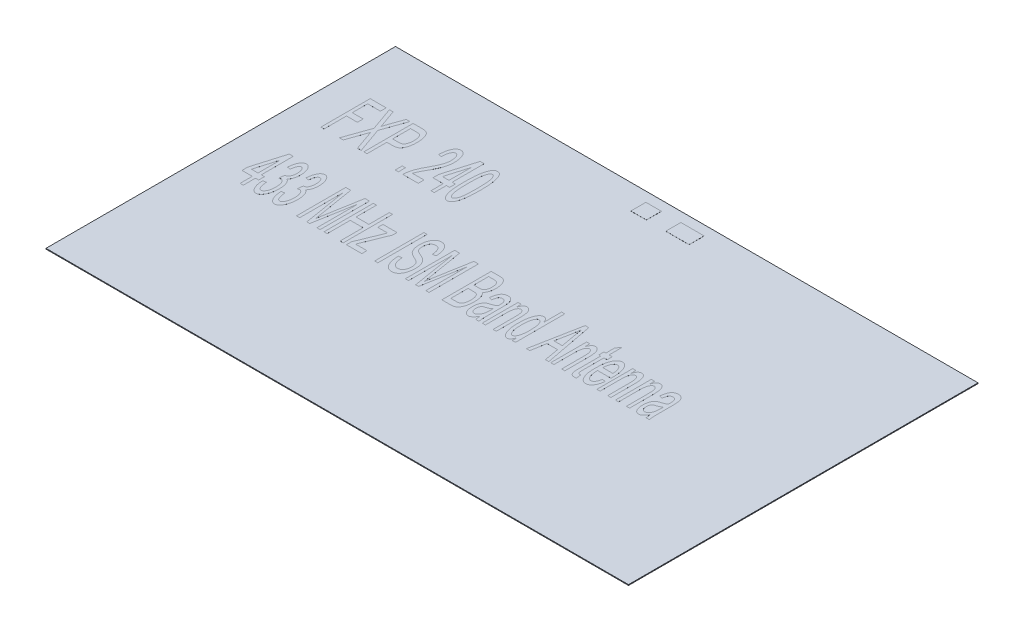
SolidWorks part; units mm, degrees
ref_plane "Front" through (0, 0, 0) normal (0, 0, 1) x (1, 0, 0)
ref_plane "Top" through (0, 0, 0) normal (0, 1, 0) x (1, 0, 0)
ref_plane "Right" through (0, 0, 0) normal (1, 0, 0) x (0, 0, -1)
sketch "Sketch1" plane through (0, 0, 0) normal (0, 1, 0) x (1, 0, 0)
  line L1 (-37.5, -22.5) -> (37.5, -22.5)
  line L2 (-37.5, -22.5) -> (-37.5, 22.5)
  line L3 (-37.5, 22.5) -> (37.5, 22.5)
  line L4 (37.5, -22.5) -> (37.5, 22.5)
  line L5 (-37.5, -22.5) -> (37.5, 22.5) construction
  line L6 (-37.5, 22.5) -> (37.5, -22.5) construction
  point P0 (0, 0)
  dimension "D1" = 75
  dimension "D2" = 45
extrude "Boss-Extrude1" add sketch "Sketch1" along normal blind 0.1
sketch "Sketch2" plane through (0, 0.1, 0) normal (0, 1, 0) x (1, 0, 0)
  line L1 (-4, 21.2387) -> (-2, 21.2387)
  line L2 (-4, 21.2387) -> (-4, 19.3008)
  line L3 (-4, 19.3008) -> (-2, 19.3008)
  line L4 (-2, 21.2387) -> (-2, 19.3008)
  line L5 (-4, 21.2387) -> (-2, 19.3008) construction
  line L6 (-4, 19.3008) -> (-2, 21.2387) construction
  line L7 (0.5, 21.2387) -> (3.5, 21.2387)
  line L8 (0.5, 21.2387) -> (0.5, 19.3008)
  line L9 (0.5, 19.3008) -> (3.5, 19.3008)
  line L10 (3.5, 21.2387) -> (3.5, 19.3008)
  line L11 (0.5, 21.2387) -> (3.5, 19.3008) construction
  line L12 (0.5, 19.3008) -> (3.5, 21.2387) construction
  point P0 (-3, 20.2698)
  point P5 (2, 20.2698)
  dimension "D1" = 3
  dimension "D2" = 2
  dimension "D3" = 5
  dimension "D4" = 2
extrude "Boss-Extrude2" add sketch "Sketch2" along normal blind 0.01
sketch "Sketch3" plane through (0, 0.1, 0) normal (0, 1, 0) x (1, 0, 0)
  text T0 "FXP .240\r\n433 MHz ISM Band Antenna" font "Arial Narrow" height 6.35
extrude "Boss-Extrude3" add sketch "Sketch3" along normal blind 0.001
